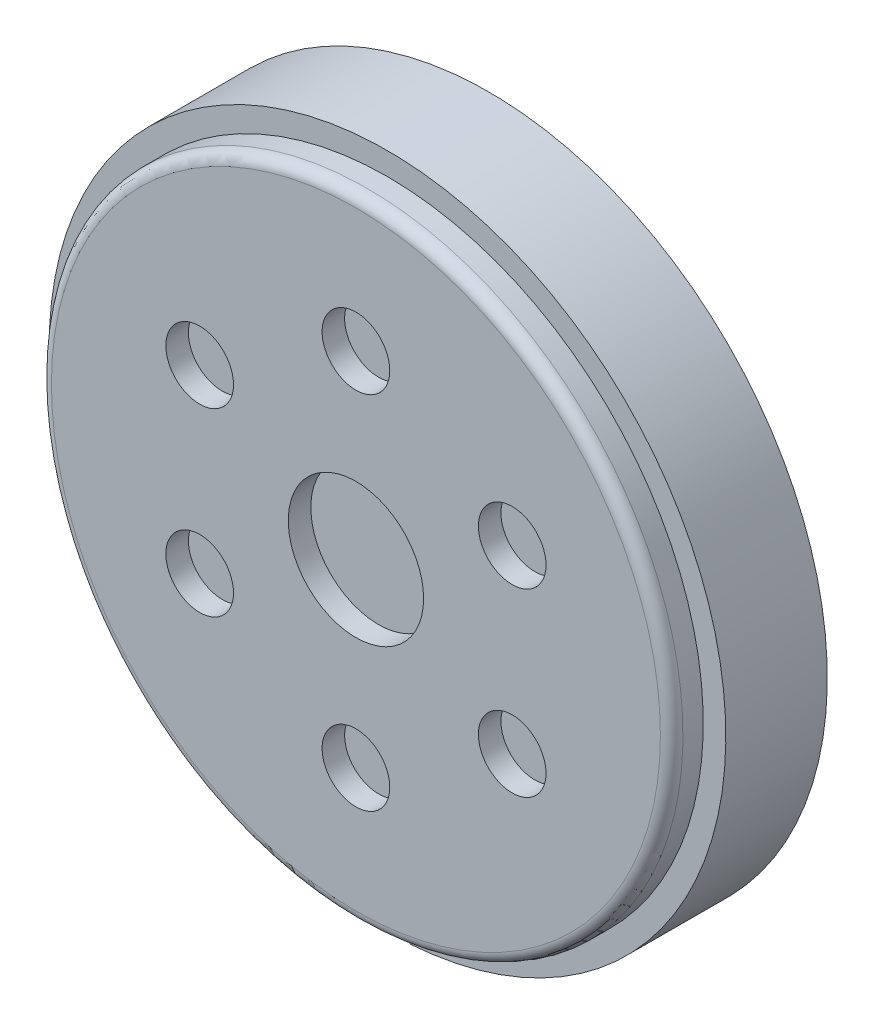
SolidWorks part; units mm, degrees
ref_plane "Спереди" through (0, 0, 0) normal (0, 0, 1) x (1, 0, 0)
ref_plane "Сверху" through (0, 0, 0) normal (0, 1, 0) x (1, 0, 0)
ref_plane "Справа" through (0, 0, 0) normal (1, 0, 0) x (0, 0, -1)
sketch "Эскиз1" plane through (0, 0, 0) normal (0, 1, 0) x (1, 0, 0)
  line L0 (0, 0) -> (0, -3.75)
  line L1 (0, -3.75) -> (-7, -3.75)
  line L2 (-7, -3.75) -> (-7, -3.05)
  line L3 (-7, -3.05) -> (-7.5, -3.05)
  line L4 (-7.5, -3.05) -> (-7.5, -0.8)
  line L5 (-7.5, -0.8) -> (-5.55, -0.8)
  line L6 (-5.55, -0.8) -> (-5.55, 0)
  line L7 (-5.55, 0) -> (0, 0)
  line L8 (0, 0) -> (0, 8.3939) construction
  dimension "D1" = 3.75
  dimension "D2" = 15
  dimension "D3" = 14
  dimension "D4" = 11.1
  dimension "D5" = 0.8
  dimension "D6" = 0.7
revolve "Повернуть1" add sketch "Эскиз1" angle 360 about L8
fillet "Скругление1" radius 0.25 2 edges at (5.55, 0, 0) (7, 0, 3.75)
sketch "Эскиз2" plane through (0, 0, 3.75) normal (0, 0, 1) x (1, 0, 0)
  line L0 (0, 0) -> (0, -4) construction
  circle A0 centre (0, 0) radius 1.5
  circle A1 centre (0, -4) radius 0.75
  circle A2 centre (-3.4641, -2) radius 0.75
  circle A3 centre (-3.4641, 2) radius 0.75
  circle A4 centre (0, 4) radius 0.75
  circle A5 centre (3.4641, 2) radius 0.75
  circle A6 centre (3.4641, -2) radius 0.75
  point P6 (3.8403, -2.346)
  point P7 (0, 0)
  point P17 (0, 0)
  dimension "D1" = 3
  dimension "D2" = 1.5
  dimension "D3" = 4
  dimension "D4" = 6
extrude "Вырез-Вытянуть1" cut sketch "Эскиз2" against normal blind 0.5
sketch "Эскиз3" plane through (0, 0, 3.05) normal (0, 0, 1) x (1, 0, 0)
  line L0 (0.5, -6.9821) -> (0.5, -7.4833)
  line L1 (-0.5, -7.4833) -> (-0.5, -6.9821)
  line L2 (0, -7) -> (0, 0) construction
  circle A0 centre (0, 0) radius 7 construction
  circle A4 centre (0, 0) radius 7.5 construction
  arc A5 (0.5, -6.9821) -> (-0.5, -6.9821) centre (0, 0) cw
  arc A6 (0.5, -7.4833) -> (-0.5, -7.4833) centre (0, 0) cw
  point P6 (0.4318, -7.4876)
  dimension "D1" = 1
extrude "Вырез-Вытянуть2" cut sketch "Эскиз3" against normal up to next
sketch "Эскиз4" plane through (0, 0, 0.8) normal (0, 0, -1) x (-1, 0, 0)
  line L2 (2.75, -5.8896) -> (2.4115, -5.1647) construction
  line L4 (-2.75, -5.8896) -> (-2.4115, -5.1647) construction
  line L5 (0, -6.5) -> (0, 0) construction
  line L6 (-2.4115, -5.1647) -> (0, 0) construction
  line L7 (-2.75, -5.8896) -> (-3.1731, -6.7957) construction
  line L8 (-4.7516, -4.4354) -> (-4.1667, -3.8895)
  line L9 (-6.4511, 0.7954) -> (-5.6572, 0.6975)
  line L10 (-5.6866, 3.1484) -> (-4.9867, 2.7609)
  line L11 (-1.237, 6.3812) -> (-1.0848, 5.5958)
  line L12 (1.237, 6.3812) -> (1.0848, 5.5958)
  line L13 (5.6866, 3.1484) -> (4.9867, 2.7609)
  line L14 (6.4511, 0.7954) -> (5.6572, 0.6975)
  line L15 (4.7516, -4.4354) -> (4.1667, -3.8895)
  arc A0 (-2.4115, -5.1647) -> (2.4115, -5.1647) centre (0, 0) ccw construction
  arc A1 (2.75, -5.8896) -> (-2.75, -5.8896) centre (0, 0) cw construction
  arc A2 (0.5, -7.4833) -> (-0.5, -7.4833) centre (0, 0) ccw construction
  arc A3 (-4.7516, -4.4354) -> (-6.4511, 0.7954) centre (0, 0) cw
  arc A4 (-5.6572, 0.6975) -> (-4.1667, -3.8895) centre (0, 0) ccw
  arc A5 (-5.6866, 3.1484) -> (-1.237, 6.3812) centre (0, 0) cw
  arc A6 (-1.0848, 5.5958) -> (-4.9867, 2.7609) centre (0, 0) ccw
  arc A7 (1.237, 6.3812) -> (5.6866, 3.1484) centre (0, 0) cw
  arc A8 (4.9867, 2.7609) -> (1.0848, 5.5958) centre (0, 0) ccw
  arc A9 (6.4511, 0.7954) -> (4.7516, -4.4354) centre (0, 0) cw
  arc A10 (4.1667, -3.8895) -> (5.6572, 0.6975) centre (0, 0) ccw
  point P10 (0, -5.7)
  point P30 (0, 0)
  dimension "D1" = 0.8
  dimension "D2" = 1
  dimension "D3" = 5.5
  dimension "D4" = 5
extrude "Вырез-Вытянуть3" cut sketch "Эскиз4" against normal blind 0.5
sketch "Эскиз5" plane through (0, 0, 0.8) normal (0, 0, -1) x (-1, 0, 0)
  line L0 (-5, -5.5902) -> (-3.7, -4.1367)
  line L1 (5, -5.5902) -> (3.7, -4.1367)
  line L2 (0, -7.5) -> (0, 0) construction
  line L3 (-3.7, -4.1367) -> (0, 0) construction
  arc A0 (0.5, -7.4833) -> (-0.5, -7.4833) centre (0, 0) ccw construction
  circle A1 centre (0, 0) radius 5.55 construction
  arc A2 (5, -5.5902) -> (-5, -5.5902) centre (0, 0) cw
  arc A3 (3.7, -4.1367) -> (-3.7, -4.1367) centre (0, 0) cw
  point P9 (3.7151, -6.5152)
  point P10 (0, -5.55)
  dimension "D1" = 10
extrude "Вырез-Вытянуть4" cut sketch "Эскиз5" against normal blind 0.8
sketch "Эскиз6" plane through (0, 0, 1.6) normal (0, 0, -1) x (-1, 0, 0)
  line L0 (-1.2943, -6.9047) -> (-1.1101, -5.9219)
  line L1 (-3.4794, -4.9188) -> (-4.0569, -5.7352)
  line L2 (-4.0569, -5.7352) -> (0, 0) construction
  line L3 (-1.0225, -5.455) -> (-1.3818, -7.3716) construction
  line L4 (-1.0225, -5.455) -> (0, 0) construction
  line L5 (-3.7, -4.1367) -> (-5, -5.5902) construction
  line L7 (-0.5, -6.9821) -> (-0.5, -7.4833) construction
  line L8 (0, -7) -> (0, 0) construction
  line L9 (3.4794, -4.9188) -> (4.0569, -5.7352)
  line L10 (1.2943, -6.9047) -> (1.1101, -5.9219)
  arc A0 (-1.1101, -5.9219) -> (-3.4794, -4.9188) centre (0, 0) cw
  arc A1 (-4.0569, -5.7352) -> (-1.2943, -6.9047) centre (0, 0) ccw
  arc A2 (-3.7, -4.1367) -> (3.7, -4.1367) centre (0, 0) ccw construction
  arc A3 (-5, -5.5902) -> (-0.5, -7.4833) centre (0, 0) ccw construction
  arc A4 (-4.0569, -5.7352) -> (-4.6833, -5.2361) centre (0, 0) cw construction
  arc A5 (-1.2943, -6.9047) -> (-0.5, -7.0072) centre (0, 0) ccw construction
  arc A6 (-0.5, -6.9821) -> (0.5, -6.9821) centre (0, 0) ccw construction
  arc A7 (1.1101, -5.9219) -> (3.4794, -4.9188) centre (0, 0) ccw
  arc A8 (4.0569, -5.7352) -> (1.2943, -6.9047) centre (0, 0) cw
  point P14 (-1.2022, -6.4133)
  point P15 (-1.2022, -6.4133)
  dimension "D1" = 3
  dimension "D2" = 1
extrude "Бобышка-Вытянуть1" add sketch "Эскиз6" along normal blind 0.2
